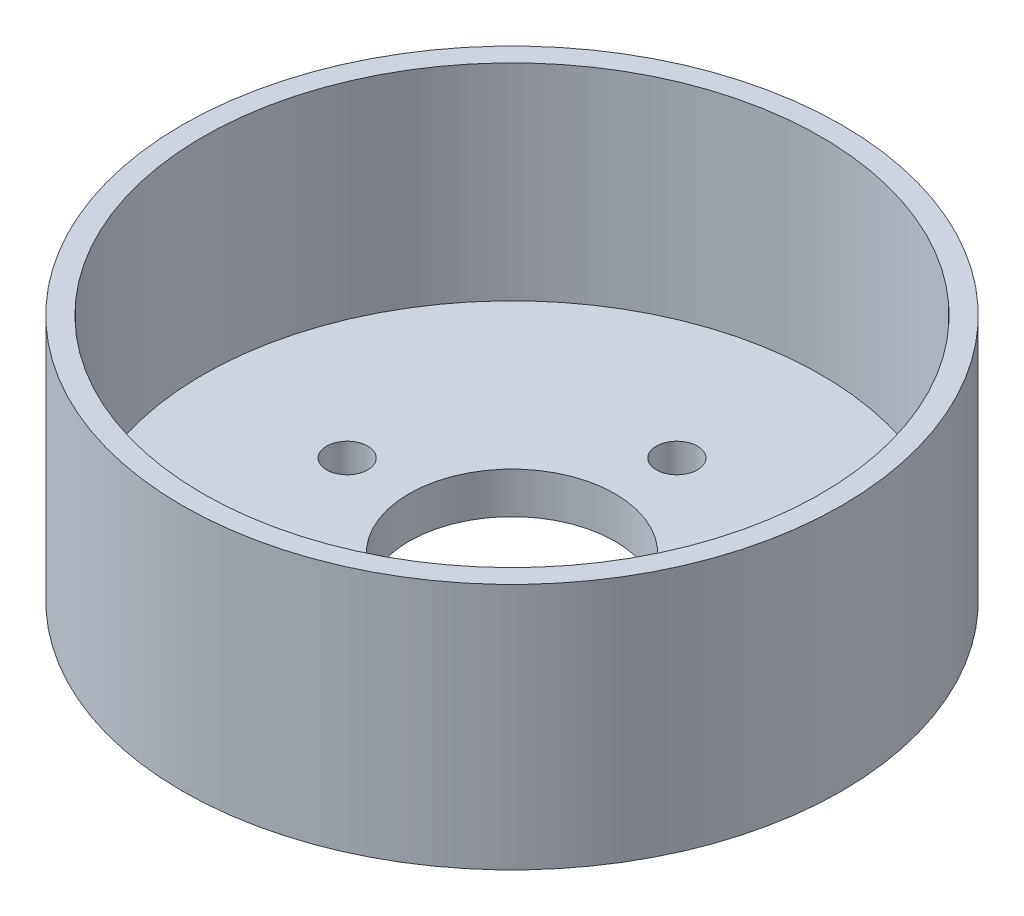
SolidWorks part; units mm, degrees
ref_plane "Front Plane" through (0, 0, 0) normal (0, 0, 1) x (1, 0, 0)
ref_plane "Top Plane" through (0, 0, 0) normal (0, 1, 0) x (1, 0, 0)
ref_plane "Right Plane" through (0, 0, 0) normal (1, 0, 0) x (0, 0, -1)
sketch "Sketch1" plane through (0, 0, 0) normal (0, 1, 0) x (1, 0, 0)
  circle A2 centre (0, 0) radius 16
extrude "Boss-Extrude1" add sketch "Sketch1" along normal blind 12.5
sketch "Sketch2" plane through (0, 12.5, 0) normal (0, 1, 0) x (1, 0, 0)
  circle A0 centre (0, 0) radius 15
extrude "Cut-Extrude1" cut sketch "Sketch2" against normal blind 10
sketch "Sketch3" plane through (0, 0, 0) normal (0, -1, 0) x (-1, 0, 0)
  circle A1 centre (0, 0) radius 5
extrude "Cut-Extrude2" cut sketch "Sketch3" against normal blind 10
sketch "Sketch4" plane through (0, 0, 0) normal (0, -1, 0) x (-1, 0, 0)
  circle A1 centre (0, 8) radius 1
  circle A2 centre (0, -8) radius 1
  circle A4 centre (-8, 0) radius 1
  circle A5 centre (8, 0) radius 1
extrude "Cut-Extrude3" cut sketch "Sketch4" against normal blind 10 contours A1 | A5 | A2 | A4
sketch "Sketch5" plane through (0, 0, 0) normal (0, -1, 0) x (1, 0, 0)
  circle A0 centre (0, 0) radius 16
extrude "Cut-Extrude4" cut sketch "Sketch5" against normal blind 0.5
